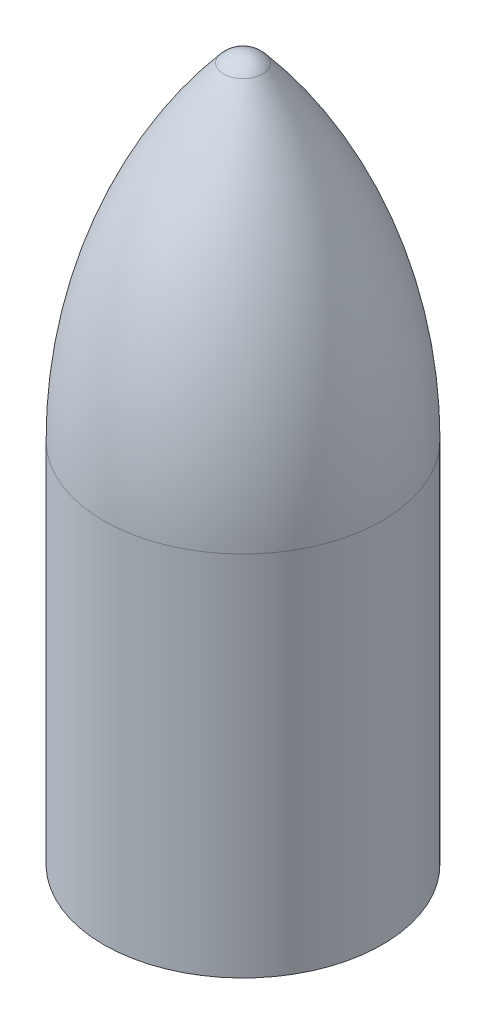
SolidWorks part; units mm, degrees
ref_plane "Front Plane" through (0, 0, 0) normal (0, 0, 1) x (1, 0, 0)
ref_plane "Top Plane" through (0, 0, 0) normal (0, 1, 0) x (1, 0, 0)
ref_plane "Right Plane" through (0, 0, 0) normal (1, 0, 0) x (0, 0, -1)
sketch "Sketch1" plane through (0, 0, 0) normal (0, 0, 1) x (1, 0, 0)
  line L0 (0, 255.4558) -> (0, -224.3926) construction
  line L1 (-49.53, 0) -> (-49.53, 130.556)
  line L2 (-49.53, 0) -> (0, 0)
  line L3 (0, 250) -> (0, 0)
  arc A0 (-49.53, 130.556) -> (-6.9023, 246.8016) centre (130.2847, 130.556) cw
  arc A1 (-6.9023, 246.8016) -> (0, 250) centre (0, 240.953) cw
  dimension "D1" = 250
  dimension "D2" = 49.53
  dimension "D3" = 130.556
revolve "Revolve1" add sketch "Sketch1" angle 360 about L0
shell "Shell1" thickness 2.54
